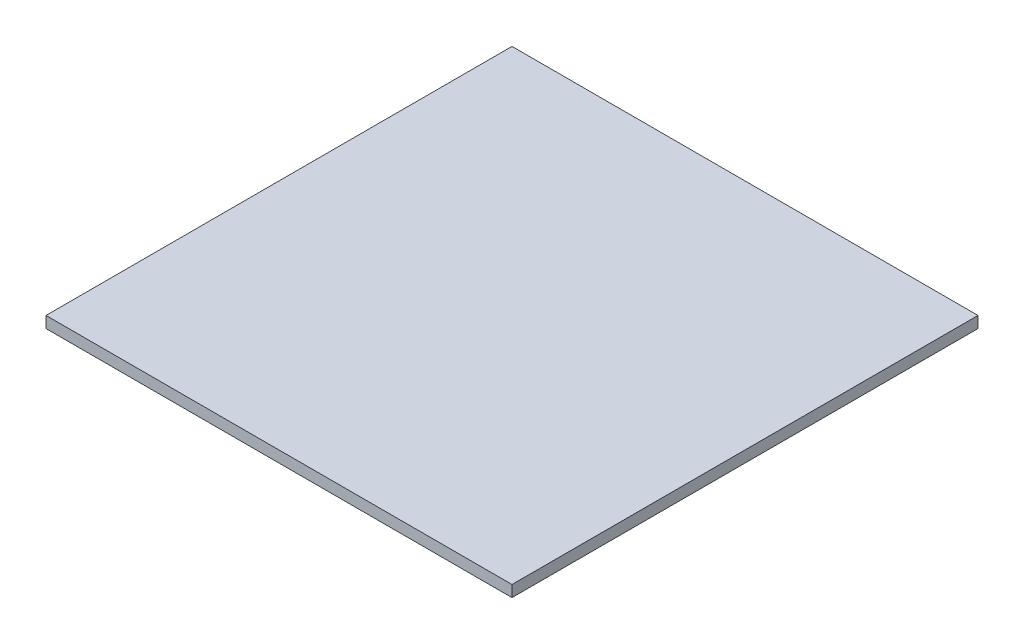
SolidWorks part; units mm, degrees
material "Acrylic (Medium-high impact)"
ref_plane "Front Plane" through (0, 0, 0) normal (0, 0, 1) x (1, 0, 0)
ref_plane "Top Plane" through (0, 0, 0) normal (0, 1, 0) x (1, 0, 0)
ref_plane "Right Plane" through (0, 0, 0) normal (1, 0, 0) x (0, 0, -1)
sketch "Sketch2" plane through (0, 0, 0) normal (0, 1, 0) x (1, 0, 0)
  line L1 (-520.7, 520.7) -> (520.7, 520.7)
  line L2 (-520.7, 520.7) -> (-520.7, -520.7)
  line L3 (-520.7, -520.7) -> (520.7, -520.7)
  line L4 (520.7, 520.7) -> (520.7, -520.7)
  line L5 (-520.7, 520.7) -> (520.7, -520.7) construction
  line L6 (-520.7, -520.7) -> (520.7, 520.7) construction
  point P0 (0, 0)
extrude "Boss-Extrude1" add sketch "Sketch2" along normal blind 25.4
